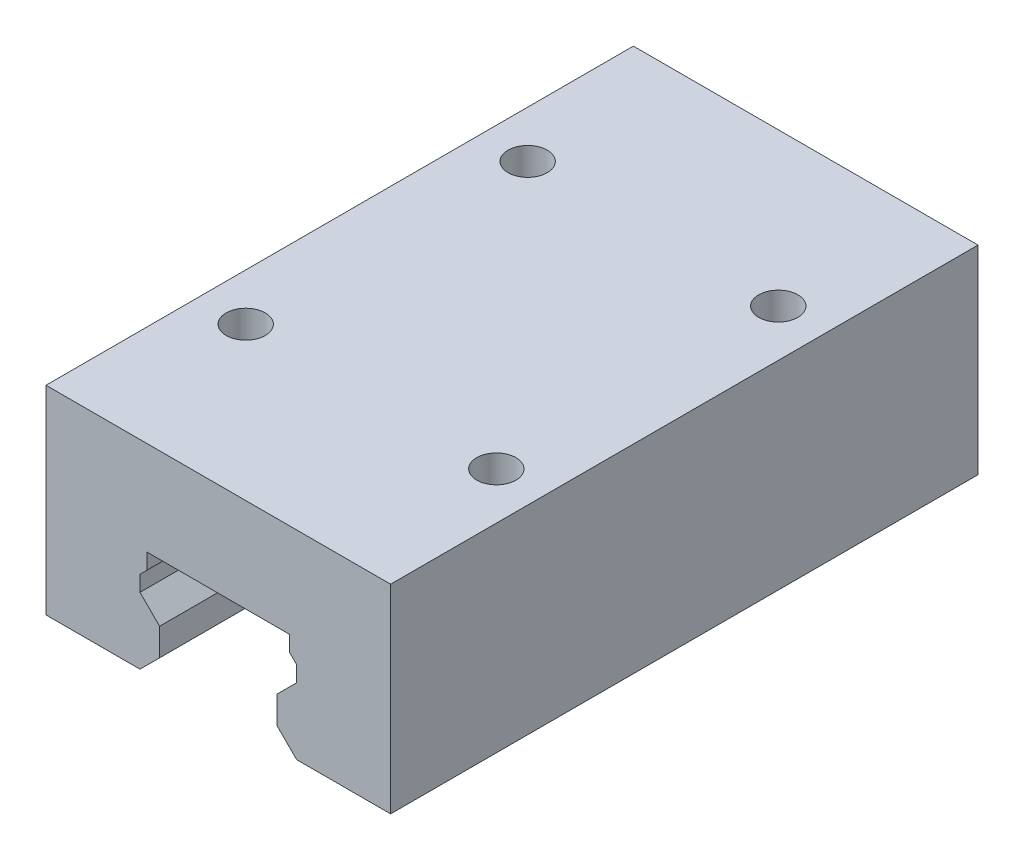
SolidWorks part; units mm, degrees
ref_plane "Frontal Plane" through (0, 0, 0) normal (0, 0, 1) x (1, 0, 0)
ref_plane "Horizontal Plane" through (0, 0, 0) normal (0, 1, 0) x (1, 0, 0)
ref_plane "Profile Plane" through (0, 0, 0) normal (1, 0, 0) x (0, 0, -1)
sketch "Sketch1" plane through (0, 0, 0) normal (0, 0, 1) x (1, 0, 0)
  line L0 (0, 17.4565) -> (0, -34.2437) construction
  line L1 (-22, 0) -> (22, 0)
  line L2 (22, 0) -> (22, -25.4)
  line L3 (22, -25.4) -> (10, -25.4)
  line L4 (10, -25.4) -> (7.5, -22.9)
  line L5 (7.5, -22.9) -> (7.5, -19.4)
  line L6 (7.5, -19.4) -> (10, -16.9)
  line L7 (10, -16.9) -> (10, -14.9)
  line L8 (10, -14.9) -> (9.1, -14)
  line L9 (9.1, -14) -> (9.1, -12)
  line L10 (9.1, -12) -> (-9.1, -12)
  line L11 (-9.1, -14) -> (-9.1, -12)
  line L12 (-10, -14.9) -> (-9.1, -14)
  line L13 (-10, -16.9) -> (-10, -14.9)
  line L14 (-7.5, -19.4) -> (-10, -16.9)
  line L15 (-7.5, -22.9) -> (-7.5, -19.4)
  line L16 (-10, -25.4) -> (-7.5, -22.9)
  line L17 (-22, -25.4) -> (-10, -25.4)
  line L18 (-22, 0) -> (-22, -25.4)
  point P22 (0, -12)
  point P30 (0, 0)
  dimension "D1" = 22
  dimension "D2" = 25.4
  dimension "D3" = 10
  dimension "D4" = 12
  dimension "D5" = 3.5
  dimension "D6" = 2.5
  dimension "D7" = 135
  dimension "D8" = 2
  dimension "D9" = 2
extrude "Boss-Extrude1" add sketch "Sketch1" against normal blind 75
sketch "Sketch2" plane through (0, 0, 0) normal (0, 1, 0) x (1, 0, 0)
  line L3 (22, 75) -> (-22, 75) construction
  line L6 (22, 75) -> (22, 0) construction
  circle A0 centre (-16, 55.5) radius 2.5
  circle A1 centre (-16, 19.5) radius 2.5
  circle A2 centre (16, 55.5) radius 2.5
  circle A3 centre (16, 19.5) radius 2.5
  dimension "D1" = 5
  dimension "D2" = 36
  dimension "D3" = 19.5
  dimension "D4" = 32
  dimension "D5" = 6
extrude "Cut-Extrude1" cut sketch "Sketch2" against normal blind 6
